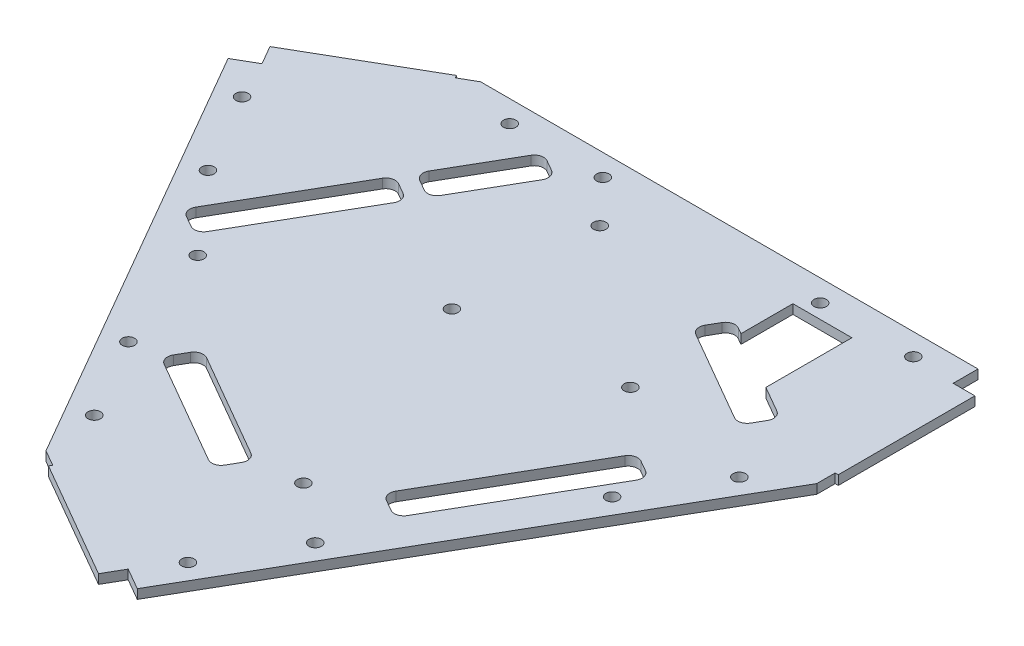
SolidWorks part; units mm, degrees
material "PVC rigide"
ref_plane "Plan de face" through (0, 0, 0) normal (0, 0, 1) x (1, 0, 0)
ref_plane "Plan de dessus" through (0, 0, 0) normal (0, 1, 0) x (1, 0, 0)
ref_plane "Plan de droite" through (0, 0, 0) normal (1, 0, 0) x (0, 0, -1)
sketch "Esquisse1" plane through (0, 0, 0) normal (0, 1, 0) x (1, 0, 0)
  line L0 (-64.1795, 79.9408) -> (98.8205, 79.9408)
  line L6 (-118.641, 45.6107) -> (-37.141, -95.5515)
  line L7 (19.8205, -125.5515) -> (101.3205, 15.6107)
  line L8 (-73.5096, 77.4408) -> (-116.8109, 52.4408)
  line L9 (103.8205, 74.9408) -> (103.8205, 24.9408)
  line L10 (12.9904, -127.3816) -> (-30.3109, -102.3816)
  line L11 (-69.1795, 79.9408) -> (-138.4615, 79.9408) construction
  line L12 (-121.141, 49.9408) -> (-138.4615, 79.9408) construction
  line L13 (-34.641, -99.8816) -> (0, -159.8816) construction
  line L14 (17.3205, -129.8816) -> (0, -159.8816) construction
  line L15 (103.8205, 79.9408) -> (138.4615, 79.9408) construction
  line L16 (103.8205, 19.9408) -> (138.4615, 79.9408) construction
  line L17 (0, -159.8816) -> (0, 79.9408) construction
  line L18 (-138.4615, 79.9408) -> (69.2308, -39.9704) construction
  line L19 (-69.2308, -39.9704) -> (138.4615, 79.9408) construction
  line L20 (12.9904, -127.3816) -> (19.8205, -125.5515)
  line L21 (17.3205, -129.8816) -> (19.8205, -125.5515) construction
  line L22 (-121.141, 49.9408) -> (-118.641, 45.6107) construction
  line L23 (-116.8109, 52.4408) -> (-118.641, 45.6107)
  line L24 (103.8205, 79.9408) -> (98.8205, 79.9408) construction
  line L25 (103.8205, 74.9408) -> (98.8205, 79.9408)
  line L26 (-30.3109, -102.3816) -> (-37.141, -95.5515)
  line L27 (-34.641, -99.8816) -> (-37.141, -95.5515) construction
  line L28 (-30.3109, -102.3816) -> (-34.641, -99.8816) construction
  line L29 (-73.5096, 77.4408) -> (-69.1795, 79.9408) construction
  line L30 (-69.1795, 79.9408) -> (-64.1795, 79.9408) construction
  line L31 (-73.5096, 77.4408) -> (-64.1795, 79.9408)
  line L32 (103.8205, 24.9408) -> (103.8205, 19.9408) construction
  line L33 (103.8205, 19.9408) -> (101.3205, 15.6107) construction
  line L34 (103.8205, 24.9408) -> (101.3205, 15.6107)
  point P12 (0, 0)
  point P24 (0, 0)
  point P34 (0, 0)
  dimension "D1" = 90
  dimension "D2" = 90
  dimension "D3" = 90
  dimension "D4" = 173
  dimension "D5" = 60
  dimension "D6" = 5
  dimension "D7" = 5
  dimension "D9" = 5
  dimension "D10" = 5
  dimension "D8" = 3
  dimension "D11" = 3
extrude "Extrusion1" add sketch "Esquisse1" along normal blind 3
sketch "Esquisse8" plane through (0, 3, 0) normal (0, 1, 0) x (1, 0, 0)
  line L0 (-116.7713, 62.3721) -> (15.6302, -166.954) construction
  line L1 (-118.641, 45.6107) -> (-37.141, -95.5515) construction
  line L2 (-60.5705, -34.9704) -> (0, 0) construction
  line L3 (-69.2308, -39.9704) -> (138.4615, 79.9408) construction
  circle A0 centre (-100.5705, 34.3116) radius 2
  circle A1 centre (80, 69.9408) radius 2
  circle A2 centre (50, 69.9408) radius 2
  circle A3 centre (-50.5705, -52.2909) radius 2
  circle A4 centre (-35.5705, -78.2717) radius 2
  circle A5 centre (-20, 69.9408) radius 2
  circle A6 centre (-50, 69.9408) radius 2
  circle A7 centre (20.5705, -104.2524) radius 2
  circle A8 centre (35.5705, -78.2717) radius 2
  circle A9 centre (-85.5705, 8.3309) radius 2
  circle A10 centre (70.5705, -17.6499) radius 2
  circle A11 centre (85.5705, 8.3309) radius 2
  point P29 (0, 0)
  point P36 (0, 0)
  point P77 (0, 0)
  dimension "D2" = 4
  dimension "D4" = 70
  dimension "D1" = 10
  dimension "D3" = 30
  dimension "D5" = 30
  dimension "D6" = 3
  dimension "D7" = 50
extrude "Enlèv. mat.-Extru.14" cut sketch "Esquisse8" against normal up to next
sketch "Esquisse10" plane through (0, 3, 0) normal (0, 1, 0) x (1, 0, 0)
  line L0 (-68.3013, -18.3013) -> (18.3013, -68.3013) construction
  line L2 (-68.3013, -18.3013) -> (-18.3013, 68.3013) construction
  line L3 (-18.3013, 68.3013) -> (68.3013, 18.3013) construction
  line L4 (68.3013, 18.3013) -> (18.3013, -68.3013) construction
  line L6 (-68.3013, -18.3013) -> (68.3013, 18.3013) construction
  line L7 (-18.3013, 68.3013) -> (18.3013, -68.3013) construction
  line L8 (19.8205, -125.5515) -> (101.3205, 15.6107) construction
  circle A0 centre (-63.5202, -17.0202) radius 2
  circle A1 centre (17.0202, -63.5202) radius 2
  circle A2 centre (42.9659, 15.8391) radius 2
  circle A3 centre (-7.6292, 8.9658) radius 2
  circle A4 centre (-7.0291, 55.9852) radius 2
  point P16 (0, 0)
  dimension "D2" = 4
  dimension "D5" = 3.5
  dimension "D10" = 38.91
  dimension "D12" = 5.03
  dimension "D1" = 100
  dimension "D3" = 3.5
  dimension "D4" = 3.5
  dimension "D6" = 3.5
  dimension "D7" = 20.71
  dimension "D8" = 14.8
  dimension "D9" = 46.05
  dimension "D11" = 15.92
extrude "Enlèv. mat.-Extru.16" cut sketch "Esquisse10" against normal through all
sketch "Esquisse12" plane through (0, 3, 0) normal (0, 1, 0) x (1, 0, 0)
  line L0 (-65.9775, 76.9408) -> (93.8205, 76.9408)
  line L1 (-65.9775, 76.9408) -> (-66.3756, 76.9408)
  line L2 (-72.0096, 74.8427) -> (-71.5096, 73.9767)
  line L3 (-71.5096, 73.9767) -> (-66.3756, 76.9408)
  line L4 (99.6214, 18.6677) -> (19.7224, -119.7213)
  line L5 (98.8205, 79.9408) -> (-64.1795, 79.9408)
  line L6 (-64.1795, 79.9408) -> (-73.5096, 77.4408)
  line L7 (-72.0096, 74.8427) -> (-110.1147, 52.8427)
  line L9 (-72.0096, 74.8427) -> (-115.3109, 49.8427) construction
  line L11 (-73.5096, 77.4408) -> (-116.8109, 52.4408)
  line L12 (-116.8109, 52.4408) -> (-118.641, 45.6107)
  line L13 (-116.8109, 52.4408) -> (-118.641, 45.6107) construction
  line L14 (-110.1147, 52.8427) -> (-106.6147, 46.7805)
  line L15 (19.8205, -125.5515) -> (101.3205, 15.6107) construction
  line L17 (-113.5429, 42.7805) -> (-106.6147, 46.7805)
  line L18 (99.6214, 18.6677) -> (99.8205, 19.0126)
  line L19 (100.8205, 24.9408) -> (99.8205, 24.9408)
  line L20 (99.8205, 24.9408) -> (99.8205, 19.0126)
  line L21 (19.8205, -125.5515) -> (101.3205, 15.6107)
  line L22 (101.3205, 15.6107) -> (103.8205, 24.9408)
  line L23 (100.8205, 24.9408) -> (100.8205, 68.9408)
  line L24 (103.8205, 24.9408) -> (103.8205, 74.9408)
  line L25 (103.8205, 74.9408) -> (98.8205, 79.9408)
  line L26 (100.8205, 68.9408) -> (93.8205, 68.9408)
  line L27 (93.8205, 76.9408) -> (93.8205, 68.9408)
  line L28 (-33.644, -95.6085) -> (-113.5429, 42.7805)
  line L29 (-33.644, -95.6085) -> (-33.4449, -95.9534)
  line L30 (-28.8109, -99.7835) -> (-28.3109, -98.9175)
  line L31 (-28.3109, -98.9175) -> (-33.4449, -95.9534)
  line L32 (-118.641, 45.6107) -> (-37.141, -95.5515)
  line L33 (-37.141, -95.5515) -> (-30.3109, -102.3816)
  line L34 (-28.8109, -99.7835) -> (9.2942, -121.7835)
  line L35 (-30.3109, -102.3816) -> (12.9904, -127.3816)
  line L36 (12.9904, -127.3816) -> (19.8205, -125.5515)
  line L37 (9.2942, -121.7835) -> (12.7942, -115.7213)
  line L38 (19.7224, -119.7213) -> (12.7942, -115.7213)
  point P59 (0, 0)
  line M20 (12.9904, -127.3816) -> (19.8205, -125.5515)
  line M21 (19.8205, -125.5515) -> (101.3205, 15.6107)
  line M22 (101.3205, 15.6107) -> (103.8205, 24.9408)
  line M23 (103.8205, 24.9408) -> (103.8205, 74.9408)
  line M24 (103.8205, 74.9408) -> (98.8205, 79.9408)
  line M25 (98.8205, 79.9408) -> (-64.1795, 79.9408)
  line M26 (-64.1795, 79.9408) -> (-73.5096, 77.4408)
  line M27 (-73.5096, 77.4408) -> (-116.8109, 52.4408)
  line M28 (-116.8109, 52.4408) -> (-118.641, 45.6107)
  line M29 (-118.641, 45.6107) -> (-37.141, -95.5515)
  line M30 (-37.141, -95.5515) -> (-30.3109, -102.3816)
  line M31 (-30.3109, -102.3816) -> (12.9904, -127.3816)
  dimension "D1" = 3
extrude "Enlèv. mat.-Extru.17" cut sketch "Esquisse12" against normal through all contours L4 L38 L37 L34 L30 L31 L29 L28 L17 L14 L7 L2 L3 L1 L0 L27 L26 L23 L19 L20 L18 M31 M20 M21 M22 M23 M24 M25 M26 M27 M28 M29 M30
sketch "Esquisse13" plane through (0, 3, 0) normal (0, 1, 0) x (1, 0, 0)
  line L0 (-70.1314, -11.4711) -> (-45.1314, 31.8301)
  line L1 (-68.3013, -18.3013) -> (-18.3013, 68.3013) construction
  line L2 (-45.1314, 31.8301) -> (-53.7917, 36.8301)
  line L3 (-53.7917, 36.8301) -> (-78.7917, -6.4711)
  line L4 (-78.7917, -6.4711) -> (-70.1314, -11.4711)
  line L5 (-68.3013, -18.3013) -> (18.3013, -68.3013) construction
  line L7 (-51.2917, 41.1603) -> (-36.2917, 67.141)
  line L8 (-36.2917, 67.141) -> (-27.6314, 62.141)
  line L9 (-27.6314, 62.141) -> (-42.6314, 36.1603)
  line L10 (-42.6314, 36.1603) -> (-51.2917, 41.1603)
  line L11 (32.6314, -53.4808) -> (62.6314, -1.5192)
  line L12 (62.6314, -1.5192) -> (71.2917, -6.5192)
  line L13 (71.2917, -6.5192) -> (41.2917, -58.4808)
  line L14 (41.2917, -58.4808) -> (32.6314, -53.4808)
  line L15 (68.3013, 18.3013) -> (18.3013, -68.3013) construction
  line L16 (70.8013, 22.6314) -> (36.1603, 42.6314)
  line L17 (36.1603, 42.6314) -> (41.1603, 51.2917)
  line L18 (41.1603, 51.2917) -> (45.8039, 48.6107)
  line L19 (75.8013, 31.2917) -> (70.8013, 22.6314)
  line L20 (-18.3013, 68.3013) -> (68.3013, 18.3013) construction
  line L21 (2.8109, -65.1314) -> (-36.1603, -42.6314)
  line L22 (-36.1603, -42.6314) -> (-41.1603, -51.2917)
  line L23 (-41.1603, -51.2917) -> (-2.1891, -73.7917)
  line L24 (-2.1891, -73.7917) -> (2.8109, -65.1314)
  line L25 (64.8039, 37.641) -> (75.8013, 31.2917)
  line L26 (45.8039, 65.3424) -> (64.8039, 65.3424)
  line L27 (45.8039, 65.3424) -> (45.8039, 48.6107)
  line L29 (64.8039, 65.3424) -> (64.8039, 46.3424)
  line L30 (45.8039, 65.3424) -> (64.8039, 46.3424) construction
  line L31 (47.2419, 47.7804) -> (64.8039, 65.3424) construction
  line L32 (64.8039, 46.3424) -> (64.8039, 37.641)
  point P35 (55.3039, 55.8424)
  dimension "D5" = 30
  dimension "D1" = 50
  dimension "D2" = 10
  dimension "D3" = 5
  dimension "D4" = 5
  dimension "D6" = 5
  dimension "D7" = 10
  dimension "D8" = 5
  dimension "D9" = 20
  dimension "D10" = 60
  dimension "D11" = 5
  dimension "D12" = 10
  dimension "D13" = 40
  dimension "D14" = 15
  dimension "D15" = 45
  dimension "D16" = 5
  dimension "D17" = 10
  dimension "D19" = 19
extrude "Enlèv. mat.-Extru.18" cut sketch "Esquisse13" against normal through all
fillet "Congé1" radius 3 20 edges at (-41.1603, 1.5, 51.2917) (-36.1603, 1.5, 42.6314) (2.8109, 1.5, 65.1314) (-2.1891, 1.5, 73.7917) (32.6314, 1.5, 53.4808) (41.2917, 1.5, 58.4808) (62.6314, 1.5, 1.5192) (71.2917, 1.5, 6.5192) (36.1603, 1.5, -42.6314) (70.8013, 1.5, -22.6314) (41.1603, 1.5, -51.2917) (-36.2917, 1.5, -67.141) (-27.6314, 1.5, -62.141) (-51.2917, 1.5, -41.1603) (-42.6314, 1.5, -36.1603) (-70.1314, 1.5, 11.4711) (-45.1314, 1.5, -31.8301) (-78.7917, 1.5, 6.4711) (-53.7917, 1.5, -36.8301) (75.8013, 1.5, -31.2917)
